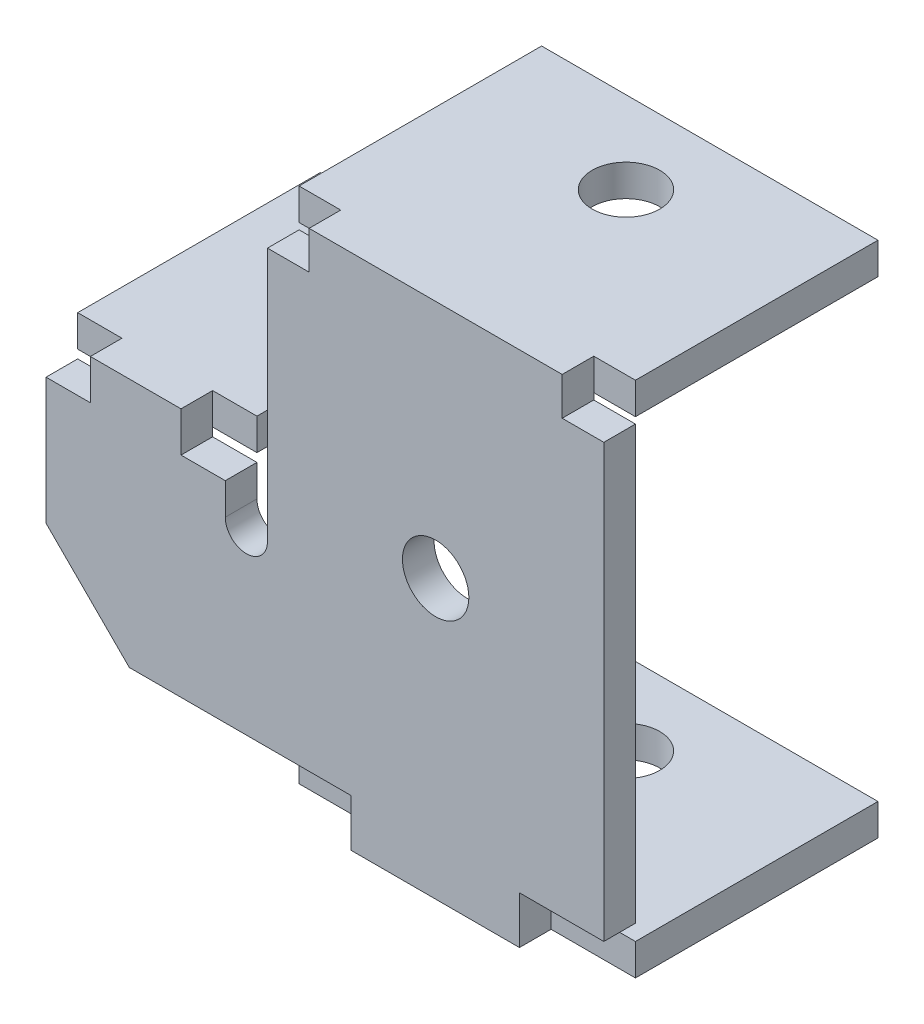
SolidWorks part; units mm, degrees
ref_plane "Front Plane" through (0, 0, 0) normal (0, 0, 1) x (1, 0, 0)
ref_plane "Top Plane" through (0, 0, 0) normal (0, 1, 0) x (1, 0, 0)
ref_plane "Right Plane" through (0, 0, 0) normal (1, 0, 0) x (0, 0, -1)
sketch "Sketch1" plane through (0, 0, 0) normal (0, 0, 1) x (1, 0, 0)
  line L0 (0, -10.25) -> (0, 10.25)
  line L2 (0, -55) -> (0, 55) construction
  line L3 (0, -10.25) -> (-4, -10.25)
  line L4 (-4, -10.25) -> (-4, -12.5)
  line L5 (-4, -12.5) -> (-12, -12.5)
  line L6 (-12, -12.5) -> (-12, -10.25)
  line L7 (-12, -10.25) -> (-22.5, -10.25)
  line L8 (-22.5, -10.25) -> (-26.45, -6.3)
  line L9 (-26.45, -6.3) -> (-26.45, -0.3)
  line L10 (-26.45, -0.3) -> (-24.35, -0.3)
  line L11 (-24.35, -0.3) -> (-24.35, 1.6)
  line L12 (-24.35, 1.6) -> (-20.05, 1.6)
  line L13 (-20.05, 1.6) -> (-20.05, -0.3)
  line L14 (-20.05, -0.3) -> (-17.95, -0.3)
  line L15 (-17.95, -0.3) -> (-17.95, -1.8)
  line L16 (0, 10.25) -> (-1.975, 10.25)
  line L17 (-1.975, 10.25) -> (-1.975, 12.05)
  line L18 (-1.975, 12.05) -> (-13.975, 12.05)
  line L19 (-13.975, 12.05) -> (-13.975, 10.25)
  line L20 (-13.975, 10.25) -> (-15.95, 10.25)
  line L21 (-15.95, 10.25) -> (-15.95, -1.8)
  arc A0 (-17.95, -1.8) -> (-15.95, -1.8) centre (-16.95, -1.8) ccw
  circle A1 centre (-7.975, 0.675) radius 1.575
  point P4 (0, 0)
  dimension "D15" = 2.5
  dimension "D16" = 3.15
  dimension "D17" = 6.4
  dimension "D1" = 20.5
  dimension "D2" = 4
  dimension "D3" = 8
  dimension "D4" = 26.45
  dimension "D5" = 45
  dimension "D6" = 10.5
  dimension "D7" = 6
  dimension "D8" = 4.3
  dimension "D9" = 8.5
  dimension "D10" = 1.9
  dimension "D11" = 2.25
  dimension "D12" = 2
  dimension "D13" = 12
  dimension "D14" = 1.8
  dimension "D18" = 8
extrude "Boss-Extrude1" add sketch "Sketch1" along normal blind 1.5
sketch "Sketch2" plane through (0, 0, 0) normal (0, 0, -1) x (-1, 0, 0)
  line L0 (0, 0.825) -> (0, -0.825) construction
  line L1 (0, 12.05) -> (15.95, 12.05)
  line L2 (0, 12.05) -> (0, 10.55)
  line L3 (0, 10.55) -> (15.95, 10.55)
  line L4 (15.95, 12.05) -> (15.95, 10.55)
  line L5 (15.95, 10.25) -> (15.95, -1.8) construction
  line L6 (1.975, 12.05) -> (13.975, 12.05) construction
  line L7 (12, -12.5) -> (4, -12.5) construction
  line L8 (0, -12.5) -> (15.95, -12.5)
  line L9 (0, -12.5) -> (0, -11)
  line L10 (0, -11) -> (15.95, -11)
  line L11 (15.95, -12.5) -> (15.95, -11)
  line L12 (20.05, 1.6) -> (24.35, 1.6) construction
  line L13 (17.95, 1.6) -> (26.45, 1.6)
  line L14 (17.95, 1.6) -> (17.95, 0.1)
  line L15 (17.95, 0.1) -> (26.45, 0.1)
  line L16 (26.45, 1.6) -> (26.45, 0.1)
  line L17 (26.45, -0.3) -> (26.45, -6.3) construction
  line L18 (17.95, -1.8) -> (17.95, -0.3) construction
  dimension "D1" = 1.5
  dimension "D2" = 1.5
  dimension "D3" = 1.5
extrude "Boss-Extrude2" add sketch "Sketch2" along normal blind 11.5
sketch "Sketch3" plane through (0, 12.05, 0) normal (0, 1, 0) x (1, 0, 0)
  line L2 (-15.95, 11.5) -> (0, 11.5) construction
  line L5 (-15.95, 11.5) -> (-15.95, 0) construction
  line L7 (-26.45, 11.5) -> (-26.45, 0) construction
  circle A0 centre (-8.05, 7.6) radius 1.6
  circle A1 centre (-22.45, 7.6) radius 1.6
  dimension "D1" = 3.2
  dimension "D2" = 3.2
  dimension "D3" = 2.3
  dimension "D4" = 6.3
  dimension "D5" = 2.4
extrude "Cut-Extrude1" cut sketch "Sketch3" against normal through all
